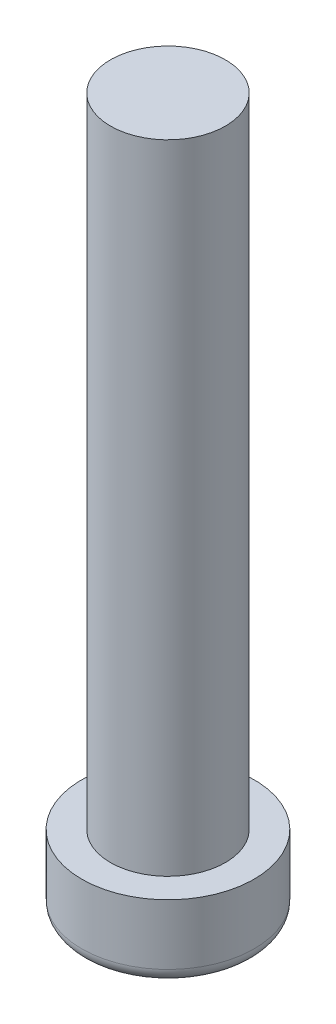
SolidWorks part; units mm, degrees
ref_plane "前视基准面" through (0, 0, 0) normal (0, 0, 1) x (1, 0, 0)
ref_plane "上视基准面" through (0, 0, 0) normal (0, 1, 0) x (1, 0, 0)
ref_plane "右视基准面" through (0, 0, 0) normal (1, 0, 0) x (0, 0, -1)
other "Configuration Table"
sketch "草图1" plane through (0, 0, 0) normal (0, 1, 0) x (1, 0, 0)
  circle A0 centre (0, 0) radius 3
  dimension "D1" = 6
extrude "凸台-拉伸1" add sketch "草图1" along normal blind 2.6
sketch "草图2" plane through (0, 2.6, 0) normal (0, 1, 0) x (1, 0, 0)
  circle A0 centre (0, 0) radius 2
  dimension "D1" = 4
extrude "凸台-拉伸2" add sketch "草图2" along normal blind 22.2
fillet "圆角1" radius 0.5 1 edges at (0, 0, 3)
